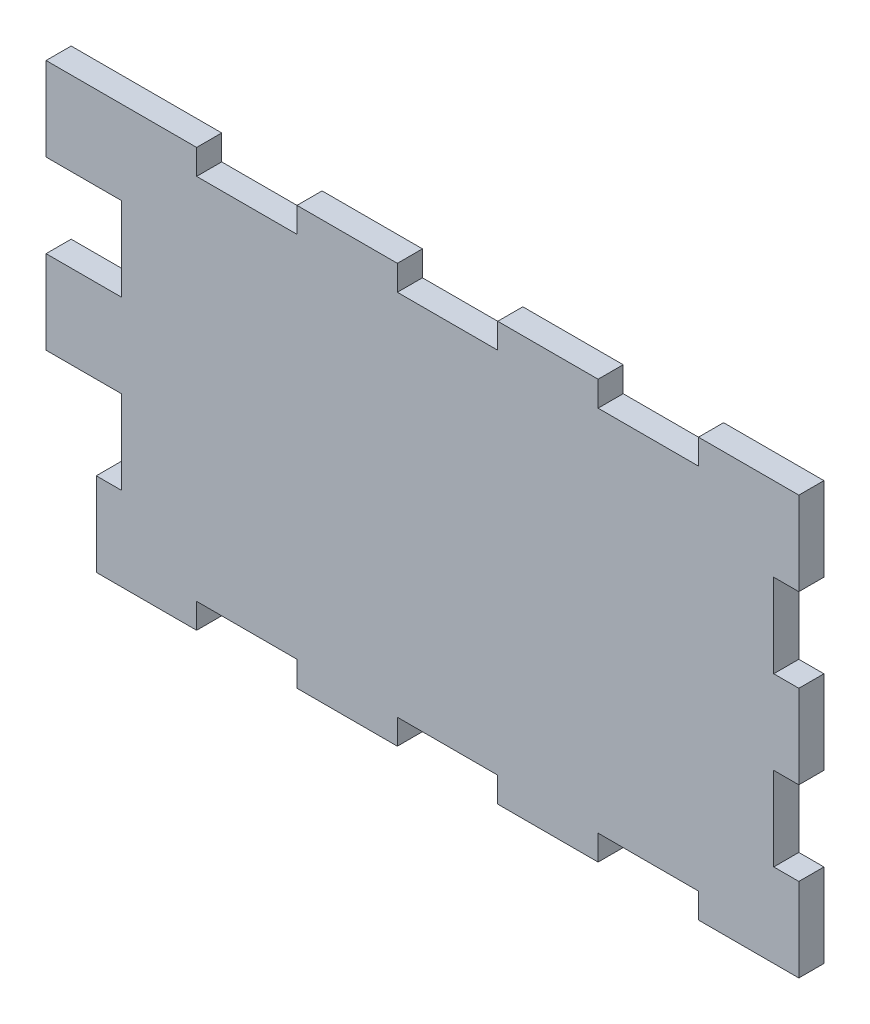
SolidWorks part; units mm, degrees
material "Balsa"
ref_plane "Front" through (0, 0, 0) normal (0, 0, 1) x (1, 0, 0)
ref_plane "Top" through (0, 0, 0) normal (0, 1, 0) x (1, 0, 0)
ref_plane "Right" through (0, 0, 0) normal (1, 0, 0) x (0, 0, -1)
sketch "Esboço4" plane through (0, 0, 0) normal (0, 0, 1) x (1, 0, 0)
  line L1 (42, -25) -> (-42, -25)
  line L2 (42, -25) -> (42, 25)
  line L3 (42, 25) -> (-42, 25)
  line L4 (-42, -25) -> (-42, 25)
  line L5 (42, -25) -> (-42, 25) construction
  line L6 (42, 25) -> (-42, -25) construction
  point P0 (0, 0)
  dimension "D1" = 84
  dimension "D2" = 50
extrude "Ressalto-extrusão2" add sketch "Esboço4" along normal blind 3
sketch "Esboço5" plane through (0, 0, 3) normal (0, 0, 1) x (1, 0, 0)
  line L0 (18, 25) -> (30, 25)
  line L1 (-18, 22) -> (-30, 22)
  line L2 (-6, 25) -> (6, 25)
  line L3 (6, 22) -> (-6, 22)
  line L4 (-30, 25) -> (-30, 22)
  line L5 (-18, 25) -> (-18, 22)
  line L6 (-6, -22) -> (6, -22)
  line L7 (-6, 25) -> (-6, 22)
  line L8 (-18, -25) -> (-30, -25)
  line L9 (6, 25) -> (6, 22)
  line L10 (6, -25) -> (-6, -25)
  line L11 (18, 25) -> (18, 22)
  line L12 (18, -22) -> (30, -22)
  line L13 (30, 25) -> (30, 22)
  line L17 (-18, -22) -> (-18, -25)
  line L19 (-6, -22) -> (-6, -25)
  line L21 (6, -22) -> (6, -25)
  line L23 (18, -22) -> (18, -25)
  line L25 (30, -22) -> (30, -25)
  line L31 (-30, -22) -> (-30, -25)
  line L32 (-30, 25) -> (-18, 25)
  line L33 (30, 22) -> (18, 22)
  line L34 (-30, -22) -> (-18, -22)
  line L35 (30, -25) -> (18, -25)
  line L37 (42, 25) -> (42, 22) [skipped]
  line L38 (42, -22) -> (42, -25) [skipped]
  dimension "D2" = 3
  dimension "D3" = 4
  dimension "D4" = 2
extrude "Corte-extrusão2" cut sketch "Esboço5" against normal up to next
sketch "Esboço6" plane through (0, 0, 0) normal (0, 0, 1) x (1, 0, 0)
  line L0 (42, 5) -> (42, 15)
  line L1 (-42, 15) -> (-42, 5)
  line L2 (-39, 5) -> (-39, 15)
  line L3 (39, 15) -> (39, 5)
  line L4 (-42, -5) -> (-42, -15)
  line L5 (42, -15) -> (42, -5)
  line L6 (-39, -15) -> (-39, -5)
  line L7 (39, -5) -> (39, -15)
  line L9 (-42, 15) -> (-39, 15)
  line L12 (39, 15) -> (42, 15)
  line L14 (39, 5) -> (42, 5)
  line L16 (39, -5) -> (42, -5)
  line L18 (39, -15) -> (42, -15)
  line L22 (-42, 5) -> (-39, 5)
  line L24 (-42, -5) -> (-39, -5)
  line L26 (-42, -15) -> (-39, -15)
  line L39 (-42, -25) -> (-39, -25) [skipped]
  line L40 (39, -25) -> (42, -25) [skipped]
  point P0 (0, 0)
  dimension "D5" = 2
  dimension "D6" = 3
extrude "Corte-extrusão4" cut sketch "Esboço6" along normal up to next
sketch "Esboço11" plane through (-42, 0, 0) normal (-1, 0, 0) x (0, 0, 1)
  line L4 (0, -5) -> (3, -5) construction
  line L5 (3, -5) -> (3, 5) construction
  line L6 (3, 5) -> (0, 5) construction
  line L7 (0, 5) -> (0, -5) construction
  line L8 (0, 15) -> (3, 15) construction
  line L9 (3, 15) -> (3, 25) construction
  line L10 (3, 25) -> (0, 25) construction
  line L11 (0, 25) -> (0, 15) construction
  line L16 (0, -5) -> (3, -5)
  line L17 (3, -5) -> (3, 5)
  line L18 (3, 5) -> (0, 5)
  line L19 (0, 5) -> (0, -5)
  line L20 (0, 15) -> (3, 15)
  line L21 (3, 15) -> (3, 25)
  line L22 (3, 25) -> (0, 25)
  line L23 (0, 25) -> (0, 15)
extrude "Ressalto-extrusão4" add sketch "Esboço11" along normal blind 6
